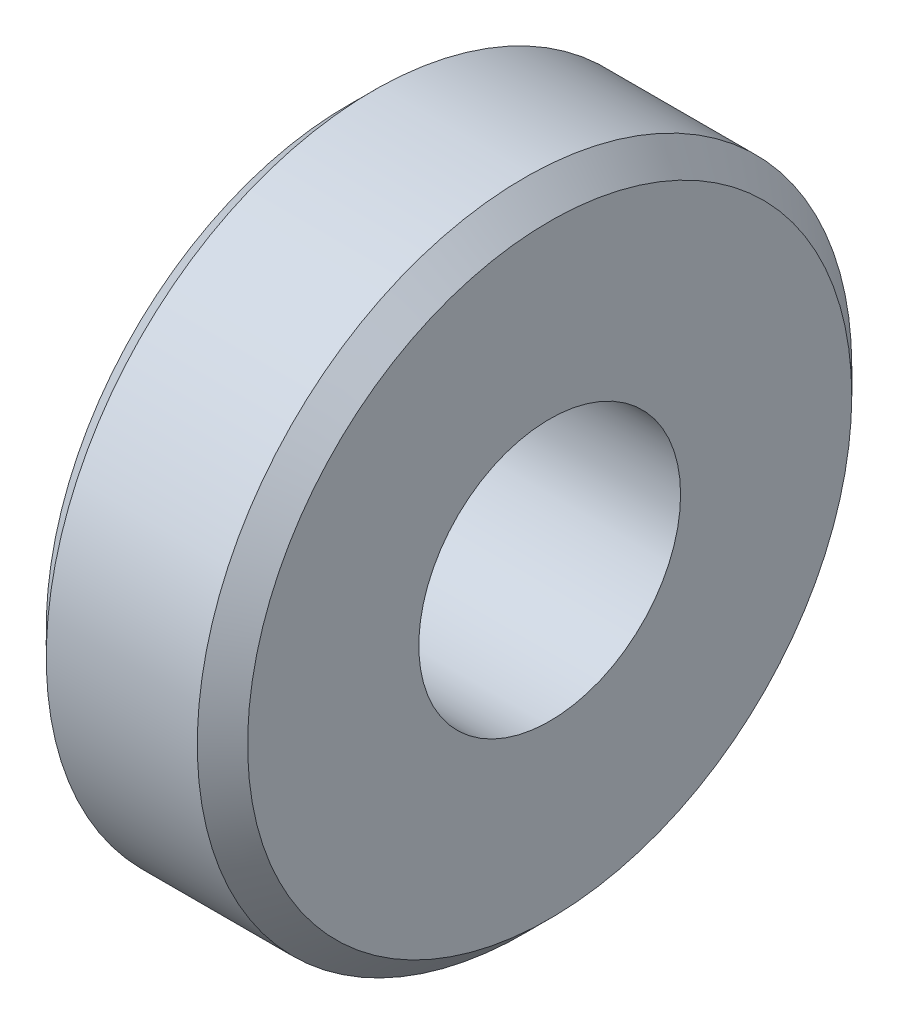
SolidWorks part; units mm, degrees
ref_plane "前视基准面" through (0, 0, 0) normal (1, 0, 0) x (0, 1, 0)
ref_plane "上视基准面" through (0, 0, 0) normal (0, 0, 1) x (0, 1, 0)
ref_plane "右视基准面" through (0, 0, 0) normal (0, 1, 0) x (-1, 0, 0)
other "Configuration Table"
sketch "草图1" plane through (0, 0, 0) normal (1, 0, 0) x (0, 1, 0)
  circle A0 centre (0, 0) radius 2.6
  circle A1 centre (0, 0) radius 6.5
  dimension "D1" = 13
  dimension "D2" = 5.2
extrude "凸台-拉伸1" add sketch "草图1" along normal blind 4
chamfer "倒角1" distance 0.5 angle 45 2 edges at (0, 0, -6.5) (4, 0, -6.5)
